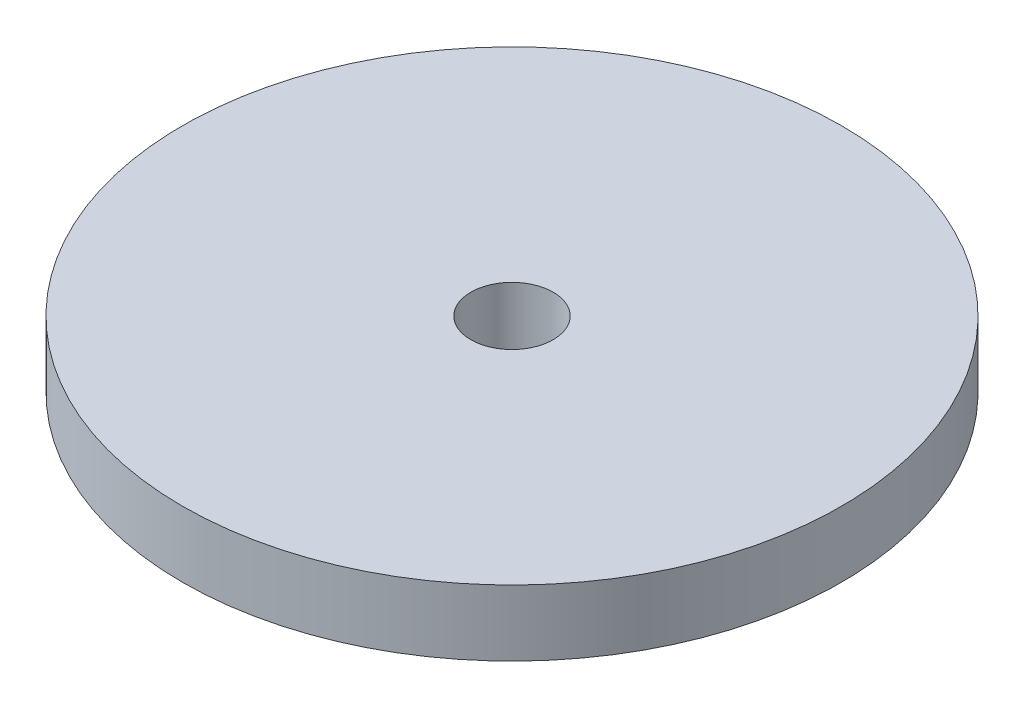
SolidWorks part; units mm, degrees
ref_plane "Front Plane" through (0, 0, 0) normal (0, 0, 1) x (1, 0, 0)
ref_plane "Top Plane" through (0, 0, 0) normal (0, 1, 0) x (1, 0, 0)
ref_plane "Right Plane" through (0, 0, 0) normal (1, 0, 0) x (0, 0, -1)
sketch "Sketch1" plane through (0, 0, 0) normal (0, 1, 0) x (1, 0, 0)
  circle A0 centre (0, 0) radius 38.1
  dimension "D1" = 76.2
extrude "Boss-Extrude1" add sketch "Sketch1" along normal blind 7.62
sketch "Sketch2" plane through (0, 7.62, 0) normal (0, 1, 0) x (1, 0, 0)
  circle A0 centre (0, 0) radius 4.7625
extrude "Cut-Extrude1" cut sketch "Sketch2" against normal blind 7.62 contours A0
